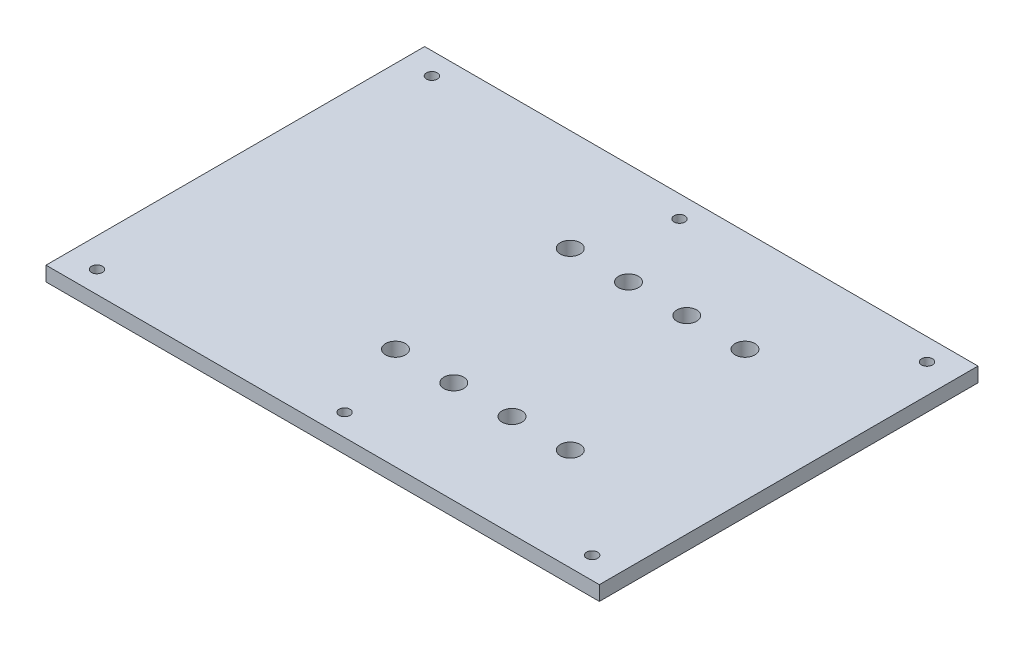
SolidWorks part; units mm, degrees
material "Balsa"
ref_plane "Front Plane" through (0, 0, 0) normal (0, 0, 1) x (1, 0, 0)
ref_plane "Top Plane" through (0, 0, 0) normal (0, 1, 0) x (1, 0, 0)
ref_plane "Right Plane" through (0, 0, 0) normal (1, 0, 0) x (0, 0, -1)
sketch "Sketch1" plane through (0, 0, 0) normal (0, 1, 0) x (1, 0, 0)
  line L1 (-241.3, 165.1) -> (241.3, 165.1)
  line L2 (-241.3, 165.1) -> (-241.3, -165.1)
  line L3 (-241.3, -165.1) -> (241.3, -165.1)
  line L4 (241.3, 165.1) -> (241.3, -165.1)
  line L5 (-241.3, 165.1) -> (241.3, -165.1) construction
  line L6 (-241.3, -165.1) -> (241.3, 165.1) construction
  point P0 (0, 0)
  dimension "D1" = 330.2
  dimension "D2" = 482.6
extrude "Boss-Extrude1" add sketch "Sketch1" along normal blind 12.7
sketch "Sketch2" plane through (0, 12.7, 0) normal (0, 1, 0) x (1, 0, 0)
  line L0 (241.3, -165.1) -> (241.3, 165.1) construction
  line L1 (-215.9, 146.05) -> (215.9, 146.05) construction
  line L2 (-215.9, 146.05) -> (-215.9, -146.05) construction
  line L3 (-215.9, -146.05) -> (215.9, -146.05) construction
  line L4 (215.9, 146.05) -> (215.9, -146.05) construction
  line L5 (-215.9, 146.05) -> (215.9, -146.05) construction
  line L6 (-215.9, -146.05) -> (215.9, 146.05) construction
  line L7 (-241.3, -165.1) -> (241.3, -165.1) construction
  line L8 (0, 146.05) -> (0, -146.05) construction
  circle A0 centre (215.9, 146.05) radius 4.7625
  circle A1 centre (-215.9, 146.05) radius 4.7625
  circle A2 centre (215.9, -146.05) radius 4.7625
  circle A3 centre (-215.9, -146.05) radius 4.7625
  circle A4 centre (0, 146.05) radius 4.7625
  circle A5 centre (0, -146.05) radius 4.7625
  point P0 (0, 0)
  dimension "D1" = 9.525
  dimension "D2" = 25.4
  dimension "D3" = 19.05
extrude "Cut-Extrude1" cut sketch "Sketch2" against normal through all both and the other way through all
sketch "Sketch4" plane through (0, 12.7, 0) normal (0, 1, 0) x (1, 0, 0)
  line L0 (-1000, 0) -> (49000, 0) construction
  line L1 (-25.4, 76.2) -> (25.4, 76.2) construction
  line L2 (25.4, 76.2) -> (76.2, 76.2) construction
  line L3 (76.2, 76.2) -> (127, 76.2) construction
  line L5 (-241.3, 165.1) -> (-241.3, -165.1) construction
  line L6 (76.2, -76.2) -> (127, -76.2) construction
  line L7 (25.4, -76.2) -> (76.2, -76.2) construction
  line L8 (-25.4, -76.2) -> (25.4, -76.2) construction
  circle A0 centre (-25.4, 76.2) radius 8.636
  circle A1 centre (25.4, 76.2) radius 8.636
  circle A2 centre (76.2, 76.2) radius 8.636
  circle A3 centre (127, 76.2) radius 8.636
  circle A4 centre (127, -76.2) radius 8.636
  circle A5 centre (76.2, -76.2) radius 8.636
  circle A6 centre (25.4, -76.2) radius 8.636
  circle A7 centre (-25.4, -76.2) radius 8.636
  dimension "D3" = 17.272
  dimension "D1" = 50.8
  dimension "D2" = 76.2
  dimension "D4" = 215.9
extrude "Cut-Extrude2" cut sketch "Sketch4" against normal through all both and the other way through all
